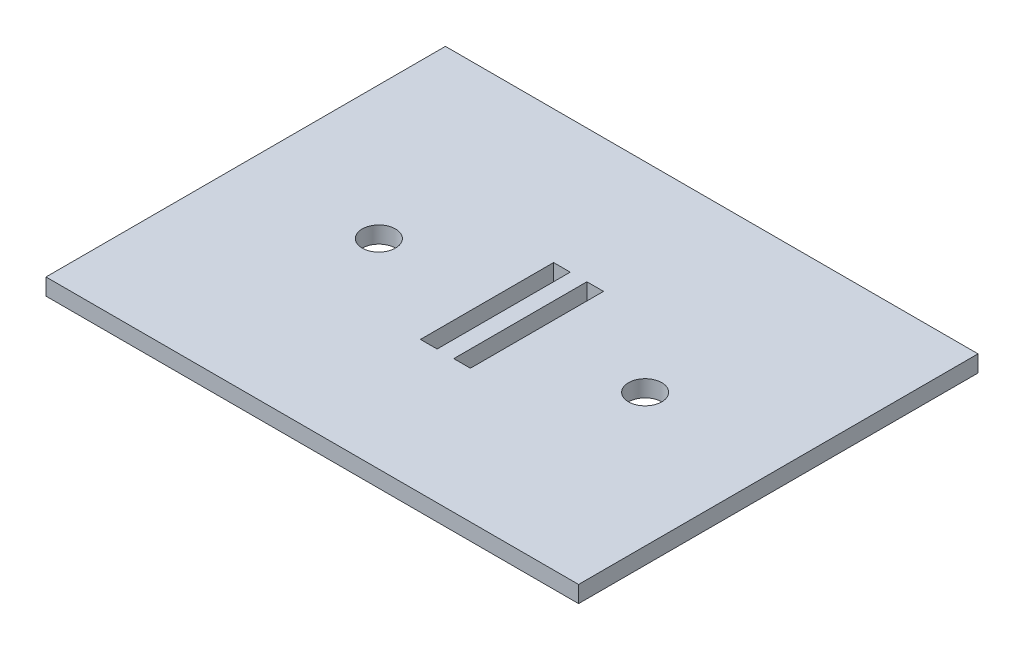
SolidWorks part; units mm, degrees
ref_plane "Front Plane" through (0, 0, 0) normal (0, 0, 1) x (1, 0, 0)
ref_plane "Top Plane" through (0, 0, 0) normal (0, 1, 0) x (1, 0, 0)
ref_plane "Right Plane" through (0, 0, 0) normal (1, 0, 0) x (0, 0, -1)
sketch "Sketch2" plane through (0, 0, 0) normal (0, 1, 0) x (1, 0, 0)
  line L0 (0, -55) -> (0, 55) construction
  line L1 (-50.8, -38.1) -> (50.8, -38.1)
  line L2 (-50.8, -38.1) -> (-50.8, 38.1)
  line L3 (-50.8, 38.1) -> (50.8, 38.1)
  line L4 (50.8, -38.1) -> (50.8, 38.1)
  line L5 (22.225, 0) -> (25.4, 0)
  line L6 (-1.5875, -12.7) -> (-4.7625, -12.7)
  line L7 (-55, 0) -> (55, 0) construction
  line L8 (-1.5875, 12.7) -> (-4.7625, 12.7)
  line L10 (-50.8, -38.1) -> (-50.8, 38.1)
  line L12 (1.5875, -12.7) -> (1.5875, 12.7)
  line L13 (-1.5875, -12.7) -> (-1.5875, 12.7)
  line L14 (-4.7625, 12.7) -> (-4.7625, -12.7)
  line L15 (1.5875, 12.7) -> (4.7625, 12.7)
  line L16 (1.5875, 12.7) -> (1.5875, -12.7)
  line L17 (1.5875, -12.7) -> (4.7625, -12.7)
  line L18 (4.7625, 12.7) -> (4.7625, -12.7)
  circle A0 centre (25.4, 0) radius 3.175
  circle A1 centre (-25.4, 0) radius 3.175
  point P1 (0, 0)
  dimension "D4" = 6.35
  dimension "D1" = 101.6
  dimension "D2" = 76.2
  dimension "D5" = 25.4
  dimension "D6" = 1.5875
  dimension "D7" = 3.175
extrude "Boss-Extrude1" add sketch "Sketch2" along normal blind 3.175 contours L1 L4 L3 L2 L15 L18 L17 L12 L14 L8 L13 L6 A0 A1
